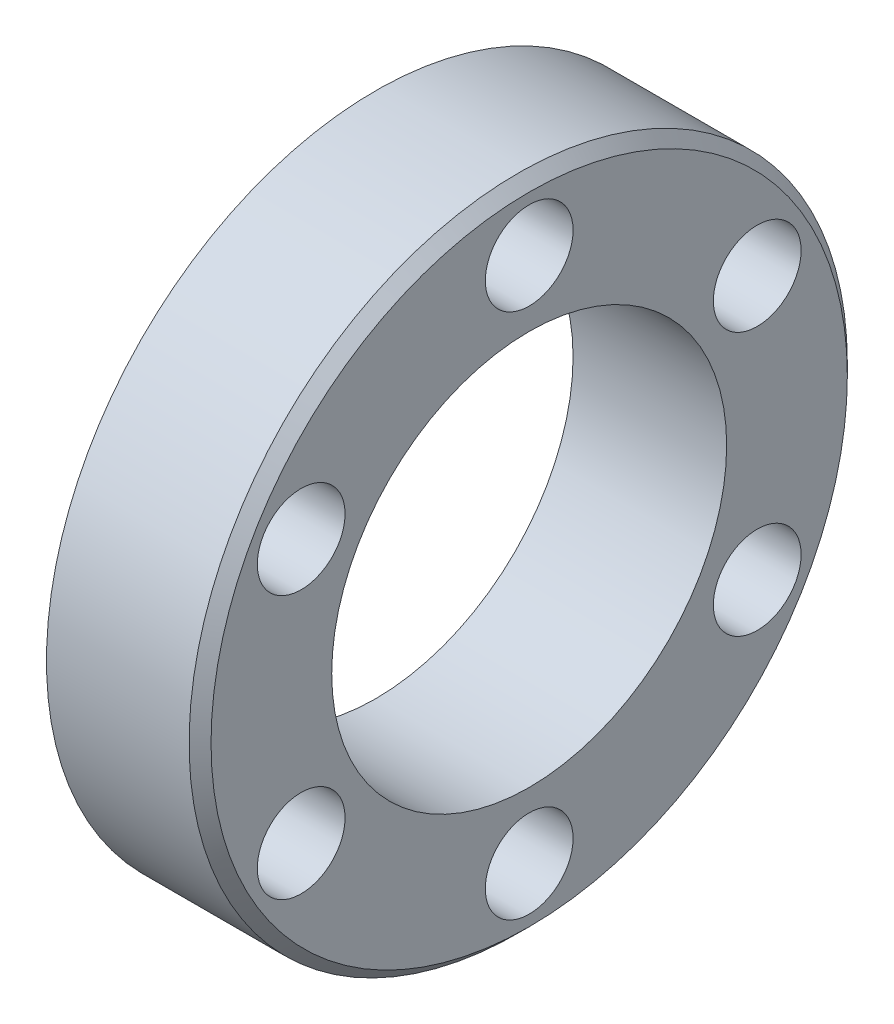
SolidWorks part; units mm, degrees
material "Plain Carbon Steel"
ref_plane "Front Plane" through (0, 0, 0) normal (0, 0, 1) x (1, 0, 0)
ref_plane "Top Plane" through (0, 0, 0) normal (0, 1, 0) x (1, 0, 0)
ref_plane "Right Plane" through (0, 0, 0) normal (1, 0, 0) x (0, 0, -1)
sketch "Sketch1" plane through (0, 0, 0) normal (1, 0, 0) x (0, 0, -1)
  circle A0 centre (0, 0) radius 15
  circle A1 centre (0, 0) radius 9
extrude "Boss-Extrude1" add sketch "Sketch1" along normal blind 7
hole_wizard "Ø4.0mm Dowel Hole1" positions "Sketch2" profile "Sketch3" hole size "Ø4.0" standard "KS"
sketch "Sketch2" plane through (7, 0, 0) normal (1, 0, 0) x (0, 0, -1)
  line L0 (0, 44.2539) -> (0, -44.2539) construction
  line L1 (55, 0) -> (-55, 0) construction
  point P0 (0, 12)
  dimension "D1" = 12
sketch "Sketch3" plane through (7, 12, 0) normal (0, 1, 0) x (0, 0, -1)
  line L0 (0, 0) -> (0, 51.2017)
  line L1 (0, 51.2017) -> (2, 50)
  line L2 (2, 50) -> (2, 0)
  line L5 (2, 0) -> (0, 0)
  line L10 (0, 51.2017) -> (-2, 50) construction
  line L11 (0, -6.35) -> (0, 107.95) construction
  dimension "Hole Dia." = 4
  dimension "Hole Depth" = 50
  dimension "Drill Angle" = 118
pattern_circular "CirPattern1" count 6 over 360 about axis through (0, 0, 0) along (1, 0, 0) of "Ø4.0mm Dowel Hole1"
chamfer "Chamfer1" distance 0.5 angle 45 1 edges at (7, 0, -15)
